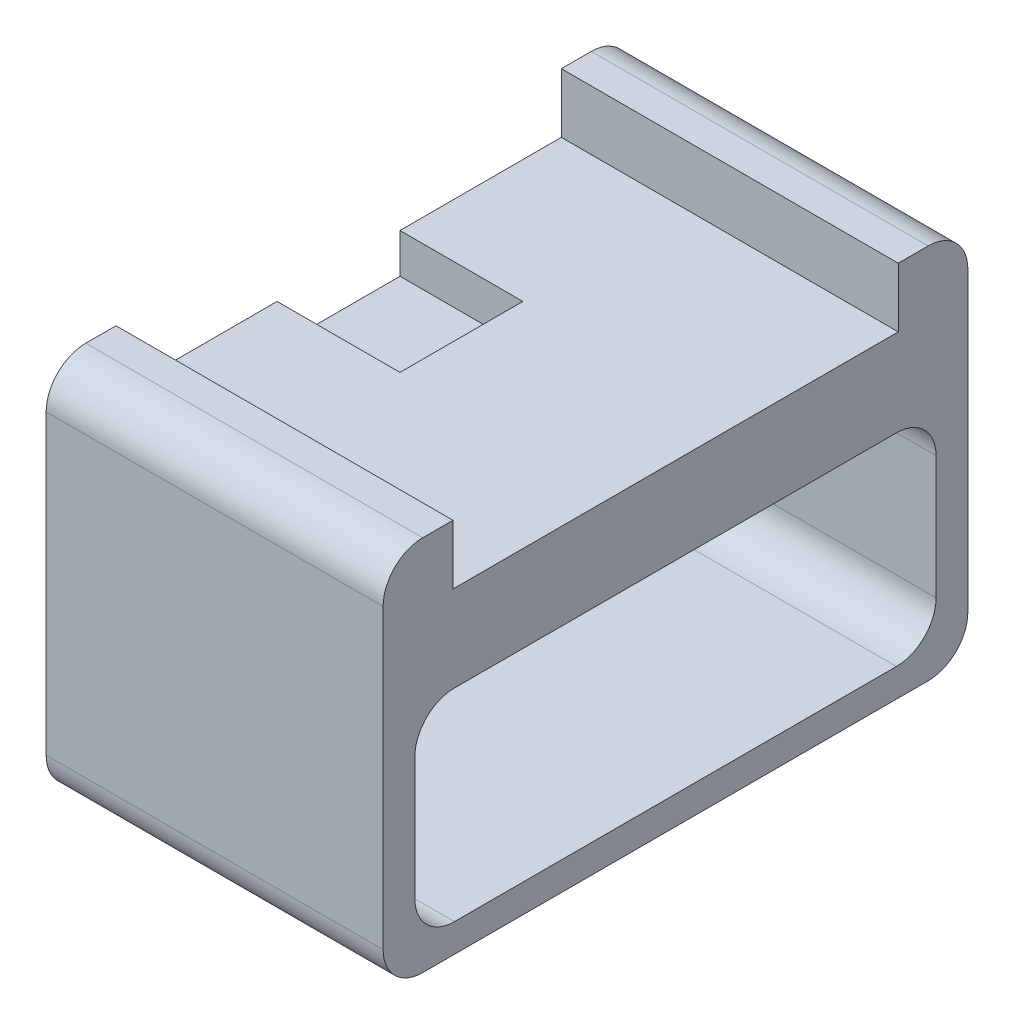
SolidWorks part; units mm, degrees
ref_plane "Front Plane" through (0, 0, 0) normal (0, 0, 1) x (1, 0, 0)
ref_plane "Top Plane" through (0, 0, 0) normal (0, 1, 0) x (1, 0, 0)
ref_plane "Right Plane" through (0, 0, 0) normal (1, 0, 0) x (0, 0, -1)
sketch "Sketch3" plane through (0, 0, 0) normal (1, 0, 0) x (0, 0, -1)
  line L0 (-12.75, -9.5) -> (12.75, -9.5)
  line L1 (-14.75, -7.5) -> (-14.75, 7.5)
  line L2 (-12.75, 9.5) -> (12.75, 9.5)
  line L3 (14.75, -7.5) -> (14.75, 7.5)
  line L4 (0, 9.5) -> (0, -9.5) construction
  line L5 (14.75, 0) -> (-14.75, 0) construction
  arc A0 (14.75, -7.5) -> (12.75, -9.5) centre (12.75, -7.5) cw
  arc A1 (-14.75, -7.5) -> (-12.75, -9.5) centre (-12.75, -7.5) ccw
  arc A2 (-12.75, 9.5) -> (-14.75, 7.5) centre (-12.75, 7.5) ccw
  arc A3 (12.75, 9.5) -> (14.75, 7.5) centre (12.75, 7.5) cw
  point P16 (0, 0)
  dimension "D3" = 2
  dimension "D1" = 19
  dimension "D2" = 25.5
extrude "Boss-Extrude1" add sketch "Sketch3" along normal blind 21
sketch "Sketch5" plane through (0, 9.5, 0) normal (0, 1, 0) x (1, 0, 0)
  line L0 (0, 12.75) -> (0, -12.75) construction
  line L1 (6.2, 3.1) -> (0, 3.1)
  line L2 (6.2, 3.1) -> (6.2, -3.1)
  line L3 (6.2, -3.1) -> (0, -3.1)
  line L4 (0, 3.1) -> (0, -3.1)
  line L5 (6.2, 0) -> (0, 0) construction
  dimension "D1" = 6.2
  dimension "D2" = 6.2
extrude "Cut-Extrude1" cut sketch "Sketch5" against normal blind 5
sketch "Sketch7" plane through (0, 0, 0) normal (-1, 0, 0) x (0, 0, 1)
  line L0 (0, 2.1353) -> (0, -8.0729) construction
  line L1 (-11.1476, -8.0729) -> (11.1476, -8.0729)
  line L2 (-13.1476, -6.0729) -> (-13.1476, 0.1353)
  line L3 (-11.1476, 2.1353) -> (11.1476, 2.1353)
  line L4 (13.1476, -6.0729) -> (13.1476, 0.1353)
  line L5 (12.75, -9.5) -> (-12.75, -9.5) construction
  arc A0 (11.1476, -8.0729) -> (13.1476, -6.0729) centre (11.1476, -6.0729) ccw
  arc A1 (11.1476, 2.1353) -> (13.1476, 0.1353) centre (11.1476, 0.1353) cw
  arc A2 (-13.1476, 0.1353) -> (-11.1476, 2.1353) centre (-11.1476, 0.1353) cw
  arc A3 (-13.1476, -6.0729) -> (-11.1476, -8.0729) centre (-11.1476, -6.0729) ccw
  point P6 (0, -2.9688)
  point P7 (0, -9.5)
  dimension "D1" = 2
extrude "Cut-Extrude2" cut sketch "Sketch7" against normal through all both and the other way through all
sketch "Sketch9" plane through (0, 9.5, 0) normal (0, 1, 0) x (1, 0, 0)
  line L0 (0, 12.75) -> (0, 3.1) construction
  line L1 (0, 11.24) -> (24.2849, 11.24)
  line L2 (0, 11.24) -> (0, -11.2248)
  line L3 (0, -11.2248) -> (24.2849, -11.2248)
  line L4 (24.2849, 11.24) -> (24.2849, -11.2248)
  line L5 (24.2849, 0.0076) -> (0, 0.0076) construction
  line L6 (6.2, -3.1) -> (6.2, 3.1) construction
  point P8 (6.2, 0)
  point P12 (6.2, -0.2283)
extrude "Cut-Extrude3" cut sketch "Sketch9" against normal blind 3
sketch "Sketch10" plane through (21, 0, 0) normal (1, 0, 0) x (0, 0, -1)
  line L1 (-15.9191, 11.2845) -> (15.8968, 11.2845)
  line L2 (-15.9191, 11.2845) -> (-15.9191, -10.3889)
  line L3 (-15.9191, -10.3889) -> (15.8968, -10.3889)
  line L4 (15.8968, 11.2845) -> (15.8968, -10.3889)
extrude "Cut-Extrude4" cut sketch "Sketch10" against normal blind 4
